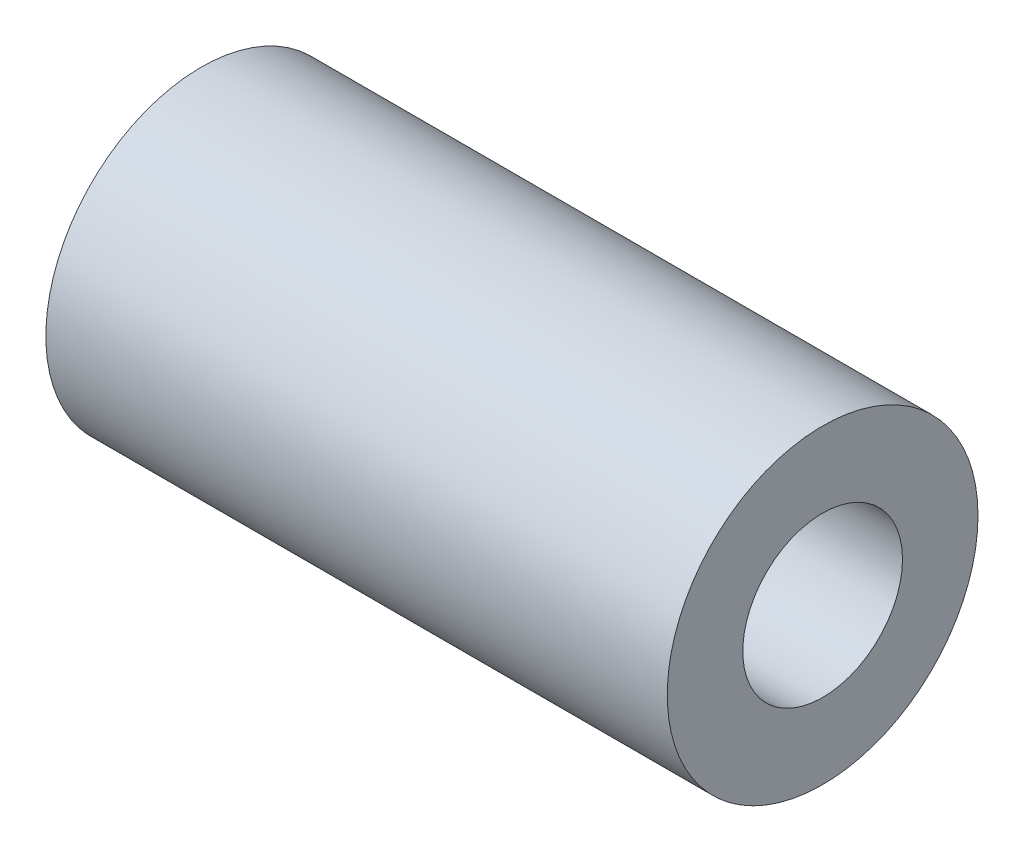
SolidWorks part; units mm, degrees
ref_plane "Front" through (0, 0, 0) normal (0, 0, 1) x (1, 0, 0)
ref_plane "Top" through (0, 0, 0) normal (0, 1, 0) x (1, 0, 0)
ref_plane "Right" through (0, 0, 0) normal (1, 0, 0) x (0, 0, -1)
sketch "Sketch1" plane through (0, 0, 0) normal (1, 0, 0) x (0, 0, -1)
  circle A0 centre (0, 0) radius 3.2639
  circle A1 centre (0, 0) radius 6.35
  dimension "D1" = 12.7
  dimension "D2" = 6.5278
extrude "Boss-Extrude1" add sketch "Sketch1" along normal blind 25.4
